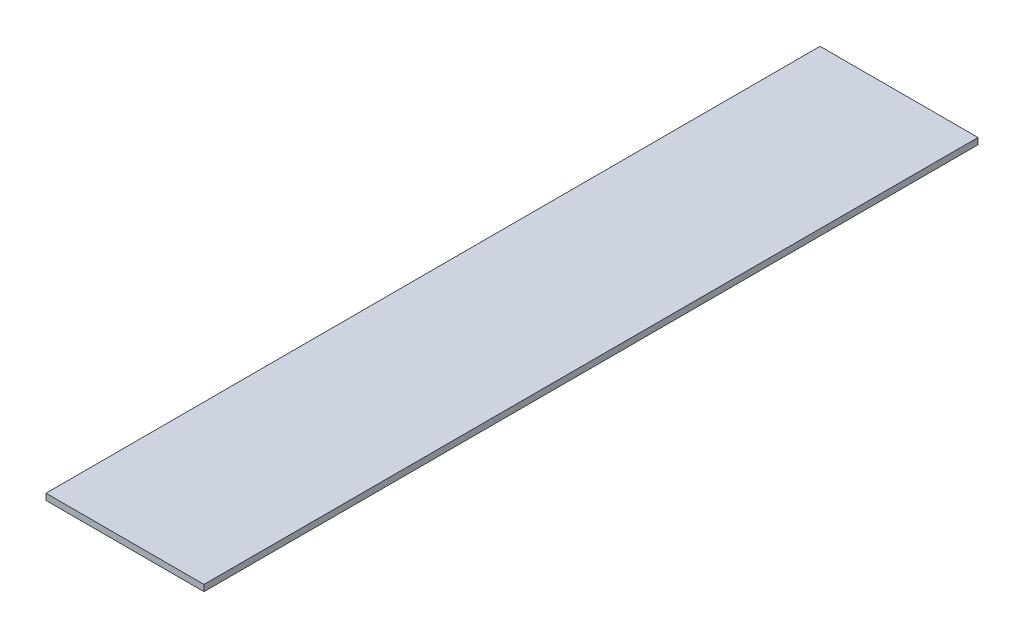
SolidWorks part; units mm, degrees
ref_plane "前视基准面" through (0, 0, 0) normal (0, 0, 1) x (1, 0, 0)
ref_plane "上视基准面" through (0, 0, 0) normal (0, 1, 0) x (1, 0, 0)
ref_plane "右视基准面" through (0, 0, 0) normal (1, 0, 0) x (0, 0, -1)
sketch "草图1" plane through (0, 0, 0) normal (0, 1, 0) x (1, 0, 0)
  line L1 (0, 0) -> (50, 0)
  line L2 (0, 0) -> (0, 245)
  line L3 (0, 245) -> (50, 245)
  line L4 (50, 0) -> (50, 245)
  dimension "D1" = 50
  dimension "D2" = 245
extrude "凸台-拉伸1" add sketch "草图1" along normal blind 2
